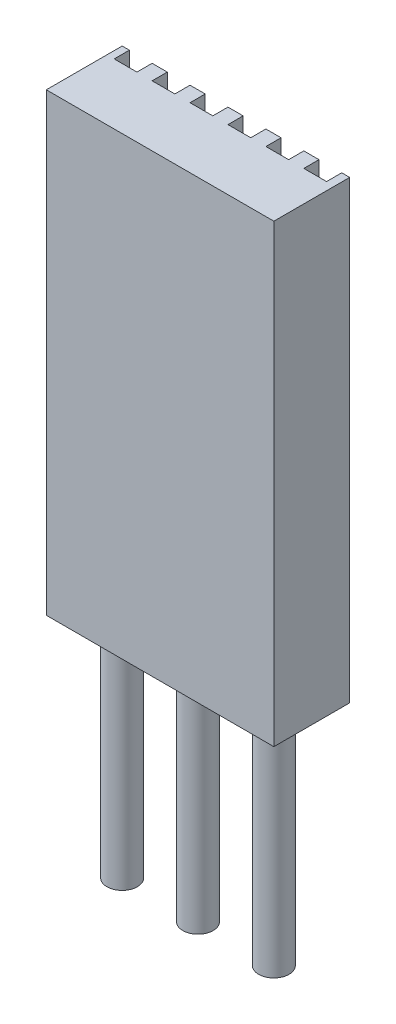
SolidWorks part; units mm, degrees
ref_plane "Front Plane" through (0, 0, 0) normal (0, 0, 1) x (1, 0, 0)
ref_plane "Top Plane" through (0, 0, 0) normal (0, 1, 0) x (1, 0, 0)
ref_plane "Right Plane" through (0, 0, 0) normal (1, 0, 0) x (0, 0, -1)
sketch "Sketch1" plane through (0, 0, 0) normal (0, 1, 0) x (1, 0, 0)
  line L0 (-10, 5) -> (20, -5) construction
  line L1 (-15, 5) -> (-14.0496, 5)
  line L2 (-15, 5) -> (-15, -5)
  line L3 (-15, -5) -> (15, -5)
  line L4 (15, 5) -> (15, -5)
  line L5 (-15, 5) -> (15, -5) construction
  line L6 (-15, -5) -> (15, 5) construction
  line L12 (-14.0496, 5) -> (-14.0496, 3)
  line L13 (-14.0496, 3) -> (-11.0496, 3)
  line L14 (-11.0496, 5) -> (-11.0496, 3)
  line L15 (-9.0496, 5) -> (-9.0496, 3)
  line L17 (-6.0496, 5) -> (-6.0496, 3)
  line L18 (-9.0496, 3) -> (-6.0496, 3)
  line L19 (-5, 5) -> (25, -5) construction
  line L20 (-4.0496, 5) -> (-4.0496, 3)
  line L22 (-1.0496, 5) -> (-1.0496, 3)
  line L23 (-4.0496, 3) -> (-1.0496, 3)
  line L24 (0, 5) -> (30, -5) construction
  line L25 (0.9504, 5) -> (0.9504, 3)
  line L27 (3.9504, 5) -> (3.9504, 3)
  line L28 (0.9504, 3) -> (3.9504, 3)
  line L29 (5, 5) -> (35, -5) construction
  line L30 (5.9504, 5) -> (5.9504, 3)
  line L32 (8.9504, 5) -> (8.9504, 3)
  line L33 (5.9504, 3) -> (8.9504, 3)
  line L34 (10, 5) -> (40, -5) construction
  line L35 (10.9504, 5) -> (10.9504, 3)
  line L37 (13.9504, 5) -> (13.9504, 3)
  line L38 (10.9504, 3) -> (13.9504, 3)
  line L39 (-11.0496, 5) -> (-9.0496, 5)
  line L40 (-6.0496, 5) -> (-4.0496, 5)
  line L41 (-1.0496, 5) -> (0.9504, 5)
  line L42 (3.9504, 5) -> (5.9504, 5)
  line L43 (8.9504, 5) -> (10.9504, 5)
  line L44 (13.9504, 5) -> (15, 5)
  point P0 (0, 0)
  dimension "D1" = 30
  dimension "D2" = 10
  dimension "D3" = 2
  dimension "D4" = 3
  dimension "D5" = 6
extrude "Boss-Extrude1" add sketch "Sketch1" along normal blind 60
sketch "Sketch2" plane through (0, 0, 0) normal (0, -1, 0) x (1, 0, 0)
  circle A0 centre (0, 0) radius 2
  circle A1 centre (10, 0) radius 2
  circle A2 centre (-10, 0) radius 2
  dimension "D1" = 4
  dimension "D2" = 2
  dimension "D3" = 2
extrude "Boss-Extrude2" add sketch "Sketch2" along normal blind 30
equation "\"30mmm\"=40"
